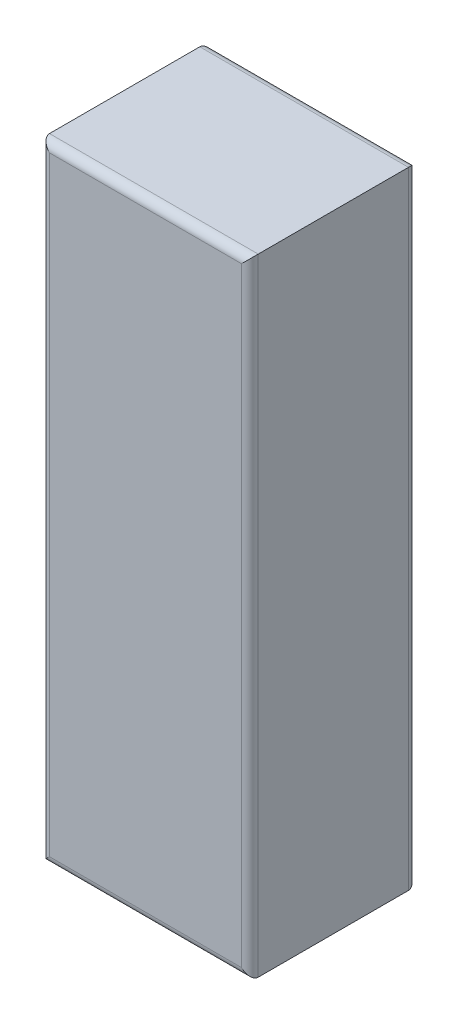
SolidWorks part; units mm, degrees
ref_plane "Front" through (0, 0, 0) normal (0, 0, 1) x (1, 0, 0)
ref_plane "Top" through (0, 0, 0) normal (0, 1, 0) x (1, 0, 0)
ref_plane "Right" through (0, 0, 0) normal (1, 0, 0) x (0, 0, -1)
sketch "Sketch1" plane through (0, 0, 0) normal (0, 1, 0) x (1, 0, 0)
  line L1 (0, 0) -> (50, 0)
  line L2 (0, 0) -> (0, 40)
  line L3 (0, 40) -> (50, 40)
  line L4 (50, 0) -> (50, 40)
  dimension "D1" = 50
  dimension "D2" = 40
extrude "Boss-Extrude1" add sketch "Sketch1" along normal blind 150
fillet "Fillet1" radius 2 8 edges at (0, 75, 0) (25, 150, 0) (50, 75, 0) (25, 0, 0) (50, 75, -40) (25, 150, -40) (0, 75, -40) (25, 0, -40)
